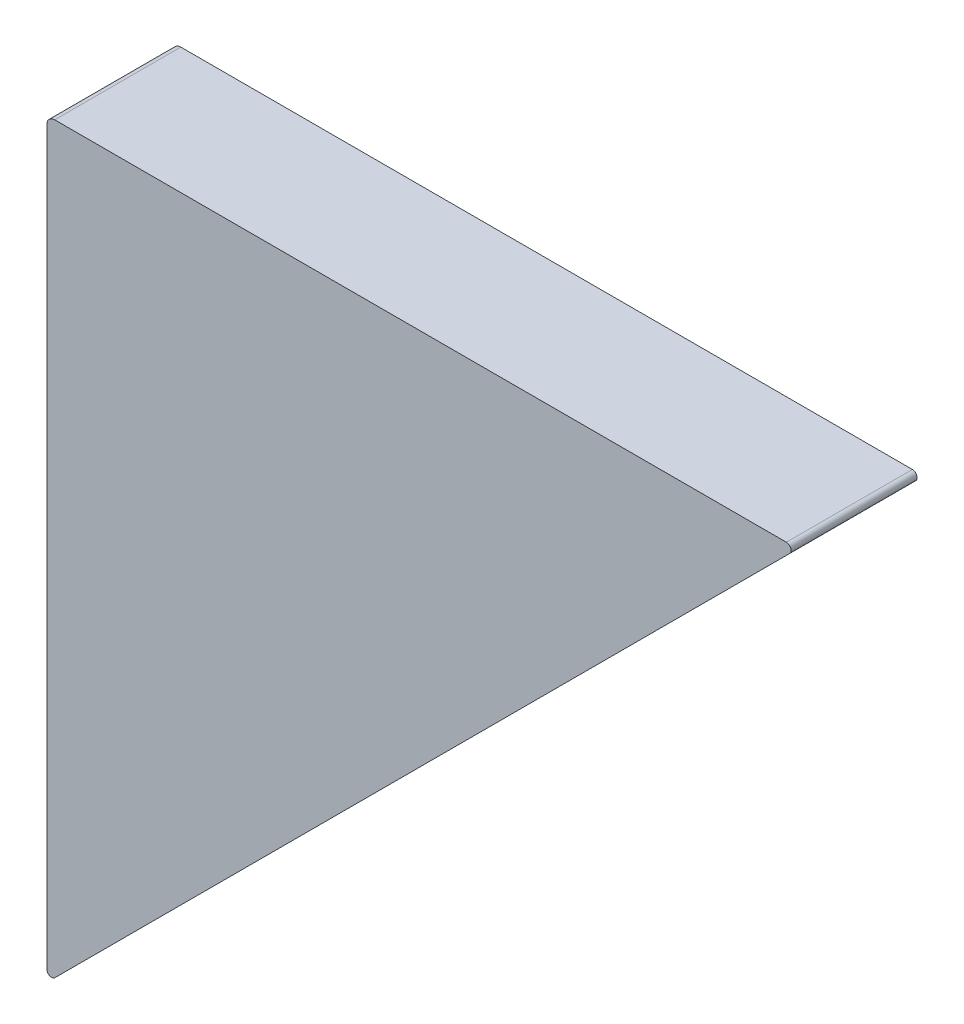
SolidWorks part; units mm, degrees
ref_plane "Front Plane" through (0, 0, 0) normal (0, 0, 1) x (1, 0, 0)
ref_plane "Top Plane" through (0, 0, 0) normal (0, 1, 0) x (1, 0, 0)
ref_plane "Right Plane" through (0, 0, 0) normal (1, 0, 0) x (0, 0, -1)
sketch "Sketch1" plane through (0, 0, 0) normal (0, 0, 1) x (1, 0, 0)
  line L0 (0, 0.7243) -> (0, 47.169)
  line L1 (0.5, 47.669) -> (46.9448, 47.669)
  line L2 (47.1569, 47.1569) -> (0.5121, 0.5121)
  arc A0 (0, 47.169) -> (0.5, 47.669) centre (0.5, 47.169) cw
  arc A1 (0, 0.7243) -> (0.5121, 0.5121) centre (0.3, 0.7243) ccw
  arc A2 (46.9448, 47.669) -> (47.1569, 47.1569) centre (46.9448, 47.369) cw
  point P8 (0, 0)
  point P11 (0.1464, 47.5226)
  dimension "D1" = 0.5
  dimension "D2" = 0.3
  dimension "D3" = 33.5
extrude "Boss-Extrude1" add sketch "Sketch1" along normal blind 8
